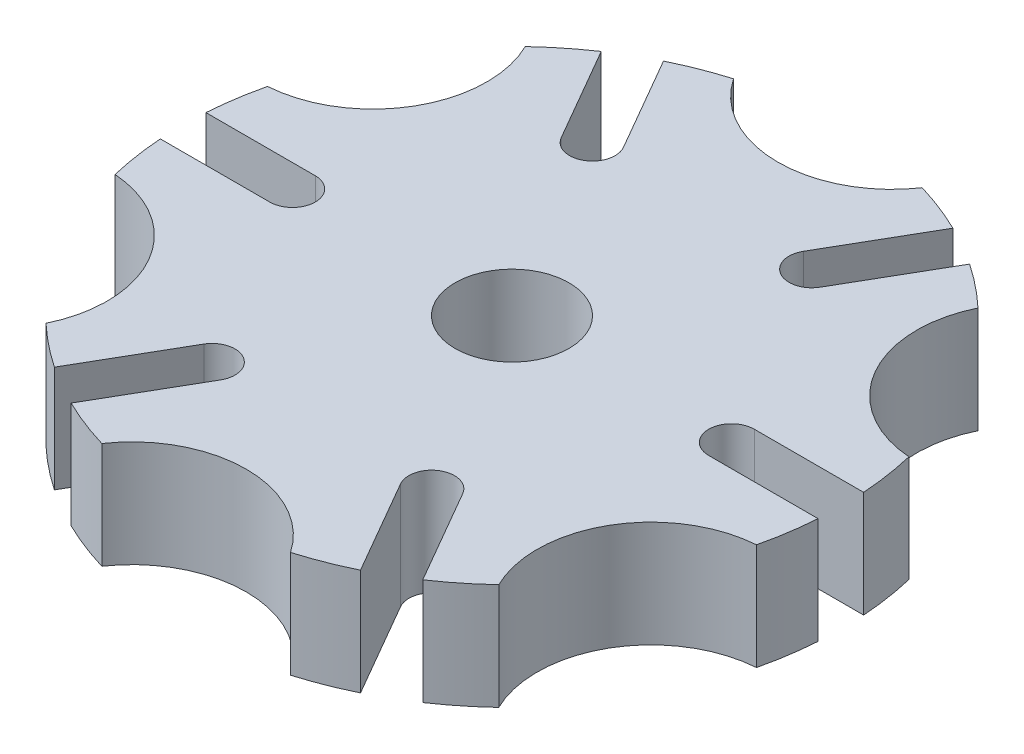
SolidWorks part; units mm, degrees
ref_plane "Front Plane" through (0, 0, 0) normal (0, 0, 1) x (1, 0, 0)
ref_plane "Top Plane" through (0, 0, 0) normal (0, 1, 0) x (1, 0, 0)
ref_plane "Right Plane" through (0, 0, 0) normal (1, 0, 0) x (0, 0, -1)
sketch "Sketch1" plane through (0, 0, 0) normal (0, 1, 0) x (1, 0, 0)
  line L0 (34.0983, -47.0601) -> (51.0589, -76.4365) construction
  line L1 (40.6068, -82.333) -> (23.706, -53.0601) construction
  line L2 (34.0983, -47.0601) -> (48.4974, -71.9999)
  line L3 (38.105, -77.9999) -> (23.706, -53.0601)
  line L4 (-23.706, -53.0601) -> (-38.105, -77.9999)
  line L5 (-48.4974, -71.9999) -> (-34.0983, -47.0601)
  line L6 (-57.8044, -6) -> (-86.6024, -6)
  line L7 (-86.6024, 6) -> (-57.8044, 6)
  line L8 (-34.0983, 47.0601) -> (-48.4974, 71.9999)
  line L9 (-38.105, 77.9999) -> (-23.706, 53.0601)
  line L10 (23.706, 53.0601) -> (38.105, 77.9999)
  line L11 (48.4974, 71.9999) -> (34.0983, 47.0601)
  line L12 (57.8044, 6) -> (86.6024, 6)
  line L13 (86.6024, -6) -> (57.8044, -6)
  arc A0 (34.0983, -47.0601) -> (23.706, -53.0601) centre (28.9022, -50.0601) ccw construction
  circle A1 centre (0, -100) radius 30 construction
  circle A2 centre (0, 0) radius 86.81 construction
  arc A3 (34.0983, -47.0601) -> (23.706, -53.0601) centre (28.9022, -50.0601) ccw
  arc A4 (24.8412, -83.1799) -> (-24.8412, -83.1799) centre (0, -100) ccw
  arc A5 (24.8412, -83.1799) -> (38.105, -77.9999) centre (0, 0) ccw
  arc A6 (48.4974, -71.9999) -> (59.6153, -63.103) centre (0, 0) ccw
  arc A7 (-23.706, -53.0601) -> (-34.0983, -47.0601) centre (-28.9022, -50.0601) ccw
  arc A8 (-59.6153, -63.103) -> (-84.4565, -20.0769) centre (-86.6025, -50) ccw
  arc A9 (-57.8044, -6) -> (-57.8044, 6) centre (-57.8044, 0) ccw
  arc A10 (-84.4565, 20.0769) -> (-59.6153, 63.103) centre (-86.6025, 50) ccw
  arc A11 (-34.0983, 47.0601) -> (-23.706, 53.0601) centre (-28.9022, 50.0601) ccw
  arc A12 (-24.8412, 83.1799) -> (24.8412, 83.1799) centre (0, 100) ccw
  arc A13 (23.706, 53.0601) -> (34.0983, 47.0601) centre (28.9022, 50.0601) ccw
  arc A14 (59.6153, 63.103) -> (84.4565, 20.0769) centre (86.6025, 50) ccw
  arc A15 (57.8044, 6) -> (57.8044, -6) centre (57.8044, 0) ccw
  arc A16 (84.4565, -20.0769) -> (59.6153, -63.103) centre (86.6025, -50) ccw
  arc A17 (-38.105, -77.9999) -> (-24.8412, -83.1799) centre (0, 0) ccw
  arc A18 (-59.6153, -63.103) -> (-48.4974, -71.9999) centre (0, 0) ccw
  arc A19 (-86.6024, -6) -> (-84.4565, -20.0769) centre (0, 0) ccw
  arc A20 (-84.4565, 20.0769) -> (-86.6024, 6) centre (0, 0) ccw
  arc A21 (-48.4974, 71.9999) -> (-59.6153, 63.103) centre (0, 0) ccw
  arc A22 (-24.8412, 83.1799) -> (-38.105, 77.9999) centre (0, 0) ccw
  arc A23 (38.105, 77.9999) -> (24.8412, 83.1799) centre (0, 0) ccw
  arc A24 (59.6153, 63.103) -> (48.4974, 71.9999) centre (0, 0) ccw
  arc A25 (86.6024, 6) -> (84.4565, 20.0769) centre (0, 0) ccw
  arc A26 (84.4565, -20.0769) -> (86.6024, -6) centre (0, 0) ccw
  point P56 (0, 0)
  dimension "D1" = 6
extrude "Boss-Extrude1" add sketch "Sketch1" along normal blind 28
sketch "Sketch2" plane through (0, 28, 0) normal (0, 1, 0) x (1, 0, 0)
  circle A0 centre (0, 0) radius 15
  dimension "D1" = 30
extrude "Cut-Extrude1" cut sketch "Sketch2" against normal through all both and the other way through all
